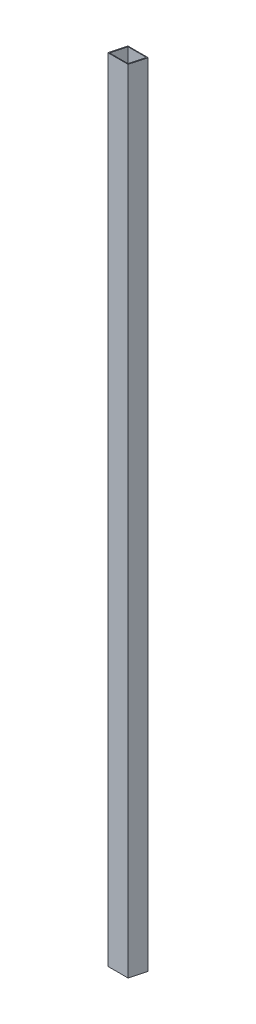
SolidWorks part; units mm, degrees
ref_plane "Front Plane" through (0, 0, 0) normal (0, 0, 1) x (1, 0, 0)
ref_plane "Top Plane" through (0, 0, 0) normal (0, 1, 0) x (1, 0, 0)
ref_plane "Right Plane" through (0, 0, 0) normal (1, 0, 0) x (0, 0, -1)
sketch "Sketch1" plane through (0, 0, 0) normal (0, 1, 0) x (1, 0, 0)
  line L0 (-11.5, 11.5) -> (11.5, 11.5)
  line L1 (-12.5, -12.5) -> (12.5, -12.5)
  line L2 (-12.5, -12.5) -> (-12.5, 12.5)
  line L3 (-12.5, 12.5) -> (12.5, 12.5)
  line L4 (12.5, -12.5) -> (12.5, 12.5)
  line L5 (-12.5, -12.5) -> (12.5, 12.5) construction
  line L6 (-12.5, 12.5) -> (12.5, -12.5) construction
  line L7 (11.5, -11.5) -> (11.5, 11.5)
  line L8 (-11.5, -11.5) -> (11.5, -11.5)
  line L9 (-11.5, -11.5) -> (-11.5, 11.5)
  point P0 (0, 0)
  dimension "D2" = 25
  dimension "D3" = 25
  dimension "D1" = 1
extrude "Boss-Extrude1" add sketch "Sketch1" along normal blind 1200
sketch "Sketch2" plane through (12.5, 0, 0) normal (1, 0, 0) x (0, 0, -1)
  line L0 (12.5, 0) -> (-12.5, 5.3139)
  line L1 (-12.5, 1200) -> (-12.5, 0) construction
  line L2 (-12.5, 5.3139) -> (-12.5, 0)
  line L3 (-12.5, 0) -> (12.5, 0)
  line L4 (12.5, 1200) -> (-12.5, 1200)
  line L5 (-12.5, 1200) -> (-12.5, 986.7609)
  line L6 (-12.5, 986.7609) -> (12.5, 981.447)
  line L7 (12.5, 1200) -> (12.5, 0) construction
  line L8 (12.5, 981.447) -> (12.5, 1200)
  point P11 (-11.5, 1000)
  point P16 (0, 0)
  point P17 (-12.5, 1000)
  point P19 (12.5, 947.4027)
  dimension "D1" = 12
  dimension "D2" = 960
extrude "Cut-Extrude1" cut sketch "Sketch2" against normal through all
